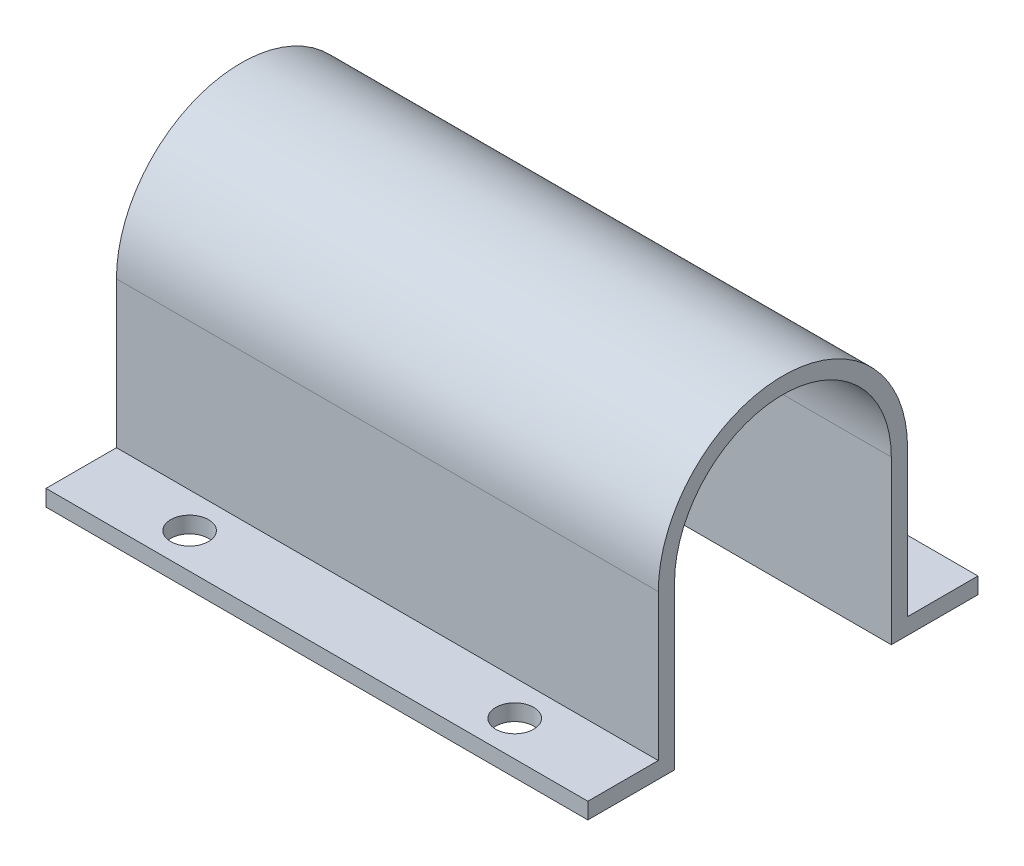
SolidWorks part; units mm, degrees
ref_plane "Front Plane" through (0, 0, 0) normal (0, 0, 1) x (1, 0, 0)
ref_plane "Top Plane" through (0, 0, 0) normal (0, 1, 0) x (1, 0, 0)
ref_plane "Right Plane" through (0, 0, 0) normal (1, 0, 0) x (0, 0, -1)
sketch "Sketch1" plane through (0, 0, 0) normal (1, 0, 0) x (0, 0, -1)
  line L0 (0, 0) -> (0, 15) construction
  line L1 (-10, 15) -> (-10, 0)
  line L2 (-10, 0) -> (-18, 0)
  line L3 (10, 15) -> (10, 0)
  line L4 (10, 0) -> (18, 0)
  line L5 (-11.5, 1.5) -> (-18, 1.5)
  line L6 (-11.5, 15) -> (-11.5, 1.5)
  line L7 (11.5, 15) -> (11.5, 1.5)
  line L8 (11.5, 1.5) -> (18, 1.5)
  line L9 (-18, 1.5) -> (-18, 0)
  line L10 (18, 1.5) -> (18, 0)
  arc A0 (10, 15) -> (-10, 15) centre (0, 15) ccw
  arc A1 (11.5, 15) -> (-11.5, 15) centre (0, 15) ccw
  dimension "D2" = 20
  dimension "D1" = 15
  dimension "D3" = 8
  dimension "D4" = 1.5
extrude "Boss-Extrude1" add sketch "Sketch1" along normal mid plane 50
sketch "Sketch2" plane through (0, 1.5, 0) normal (0, 1, 0) x (1, 0, 0)
  line L0 (-25, 14.75) -> (-15, 14.75) construction
  line L1 (-25, 18) -> (-25, 11.5) construction
  line L2 (-15, 14.75) -> (-15, -14.75) construction
  line L3 (-15, -14.75) -> (-25, -14.75) construction
  line L4 (-25, -11.5) -> (-25, -18) construction
  circle A0 centre (-15, 14.75) radius 1.75
  circle A1 centre (-15, -14.75) radius 1.75
  dimension "D2" = 3.5
  dimension "D1" = 10
extrude "Cut-Extrude1" cut sketch "Sketch2" against normal through all
mirror "Mirror1" about plane through (0, 0, 0) normal (1, 0, 0) of "Cut-Extrude1"
